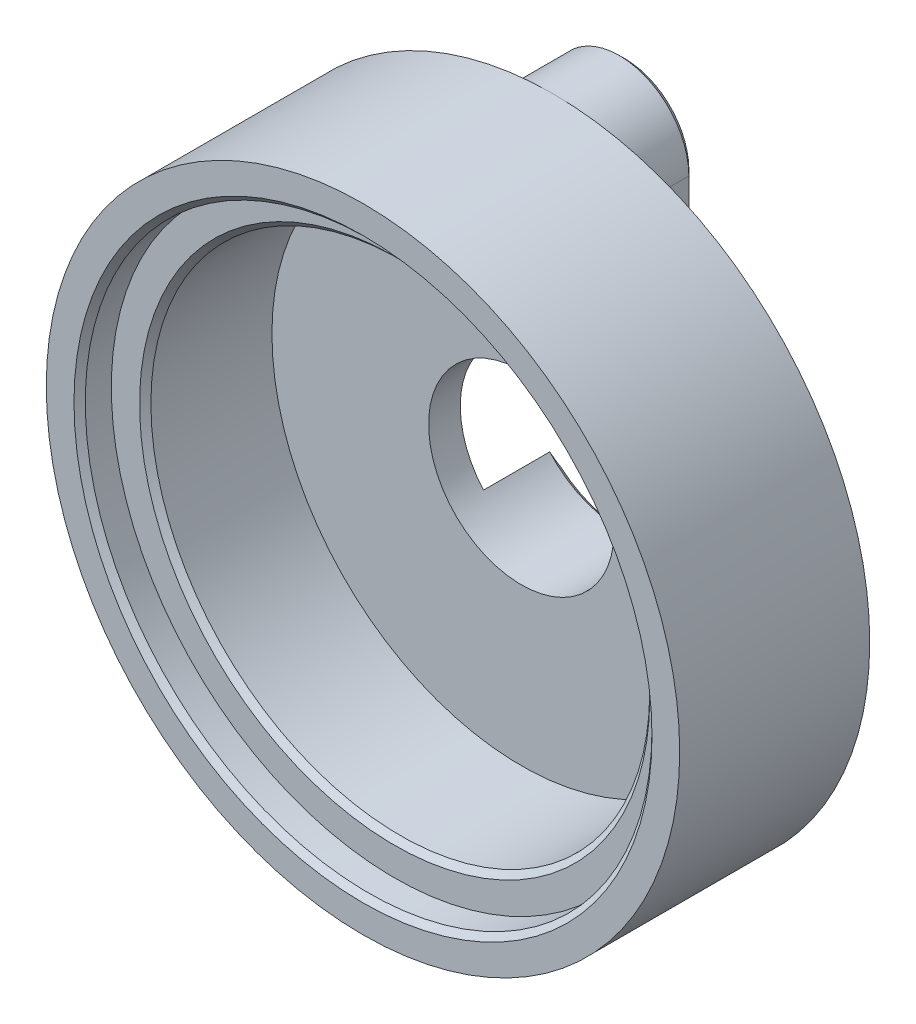
SolidWorks part; units mm, degrees
ref_plane "Front Plane" through (0, 0, 0) normal (0, 0, 1) x (1, 0, 0)
ref_plane "Top Plane" through (0, 0, 0) normal (0, 1, 0) x (1, 0, 0)
ref_plane "Right Plane" through (0, 0, 0) normal (1, 0, 0) x (0, 0, -1)
sketch "Sketch1" plane through (0, 0, 0) normal (0, 0, 1) x (1, 0, 0)
  line L0 (0, 41.6475) -> (0, -38.9605) construction
  line L1 (-51.0517, 0) -> (45.994, 0) construction
  line L2 (3.075, 10.925) -> (3.075, -10.925)
  line L3 (-3.075, 10.925) -> (-3.075, -10.925)
  arc A0 (3.075, 10.925) -> (-3.075, 10.925) centre (0, 10.925) ccw
  arc A1 (3.075, -10.925) -> (-3.075, -10.925) centre (0, -10.925) cw
  point P10 (3.075, 0)
  point P13 (-3.075, 0)
  dimension "D1" = 6.15
  dimension "D2" = 10.925
extrude "Boss-Extrude1" add sketch "Sketch1" along normal blind 3.18
sketch "Sketch2" plane through (0, 0, 3.18) normal (0, 0, 1) x (1, 0, 0)
  circle A0 centre (0, 0) radius 14
  dimension "D1" = 28
extrude "Boss-Extrude2" add sketch "Sketch2" along normal blind 8.4
sketch "Sketch3" plane through (0, 0, 11.58) normal (0, 0, 1) x (1, 0, 0)
  circle A0 centre (0, 0) radius 4.1
  dimension "D1" = 8.2
extrude "Cut-Extrude1" cut sketch "Sketch3" against normal through all
sketch "Sketch4" plane through (0, 0, 11.58) normal (0, 0, 1) x (1, 0, 0)
  circle A0 centre (0, 0) radius 11.025
  dimension "D1" = 22.05
extrude "Cut-Extrude2" cut sketch "Sketch4" against normal blind 7
sketch "Sketch5" plane through (0, 0, 11.58) normal (0, 0, 1) x (1, 0, 0)
  circle A0 centre (0, 0) radius 12.525
  dimension "D1" = 25.05
extrude "Cut-Extrude3" cut sketch "Sketch5" against normal blind 1.4
chamfer "Chamfer1" distance 0.25 angle 45 10 edges at (0, -14, 0) (3.075, -6.8184, 0) (0, -4.1, 0) (0, 4.1, 0) (-3.075, -6.8184, 0) (0, 14, 0) (-3.075, 6.8184, 0) (3.075, 6.8184, 0) (12.525, 0, 11.58) (11.025, 0, 10.18)
